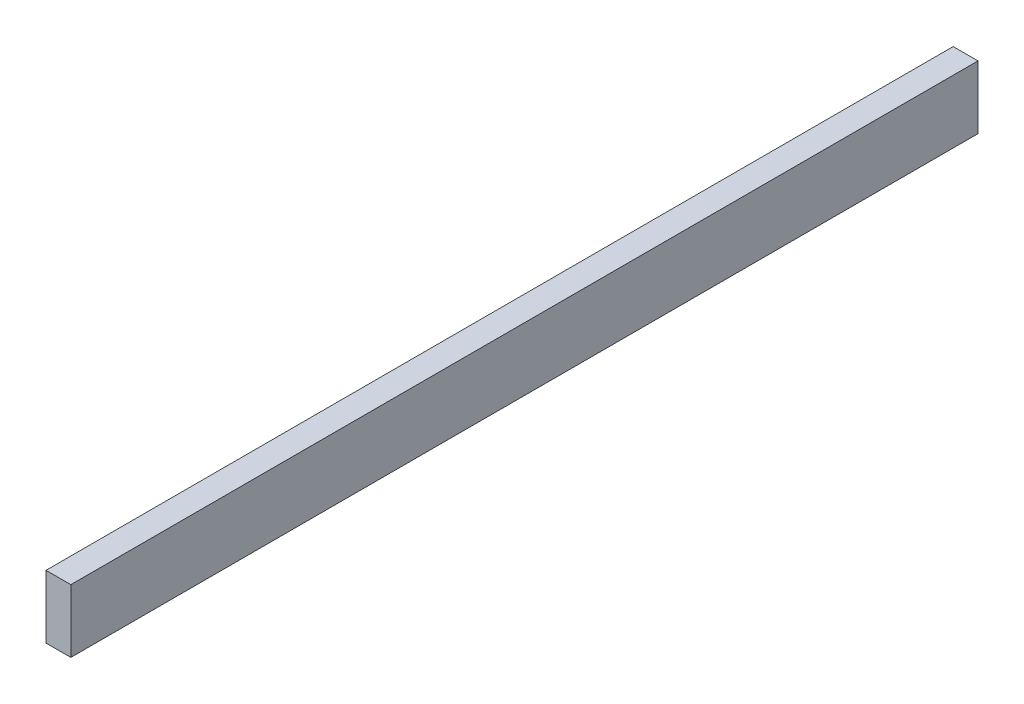
SolidWorks part; units mm, degrees
ref_plane "Front Plane" through (0, 0, 0) normal (0, 0, 1) x (1, 0, 0)
ref_plane "Top Plane" through (0, 0, 0) normal (0, 1, 0) x (1, 0, 0)
ref_plane "Right Plane" through (0, 0, 0) normal (1, 0, 0) x (0, 0, -1)
sketch "Sketch1" plane through (0, 0, 0) normal (0, 0, 1) x (1, 0, 0)
  line L1 (0, 22.86) -> (18, 22.86)
  line L2 (0, 22.86) -> (0, -22.86)
  line L3 (0, -22.86) -> (18, -22.86)
  line L4 (18, 22.86) -> (18, -22.86)
  dimension "D1" = 18
  dimension "D2" = 45.72
extrude "Boss-Extrude1" add sketch "Sketch1" against normal blind 552
sketch "Sketch2" plane through (0, 0, -552) normal (0, 0, -1) x (-1, 0, 0)
  line L0 (-18, 22.86) -> (0, 22.86) construction
  line L1 (-18, -22.86) -> (0, -22.86)
  line L2 (-18, -22.86) -> (-18, 22.86)
  line L3 (-18, 22.86) -> (0, 22.86)
  line L4 (0, -22.86) -> (0, 22.86)
  line L5 (0, 22.86) -> (0, -22.86) construction
extrude "Boss-Extrude2" add sketch "Sketch2" along normal up to surface (106 mm away)
